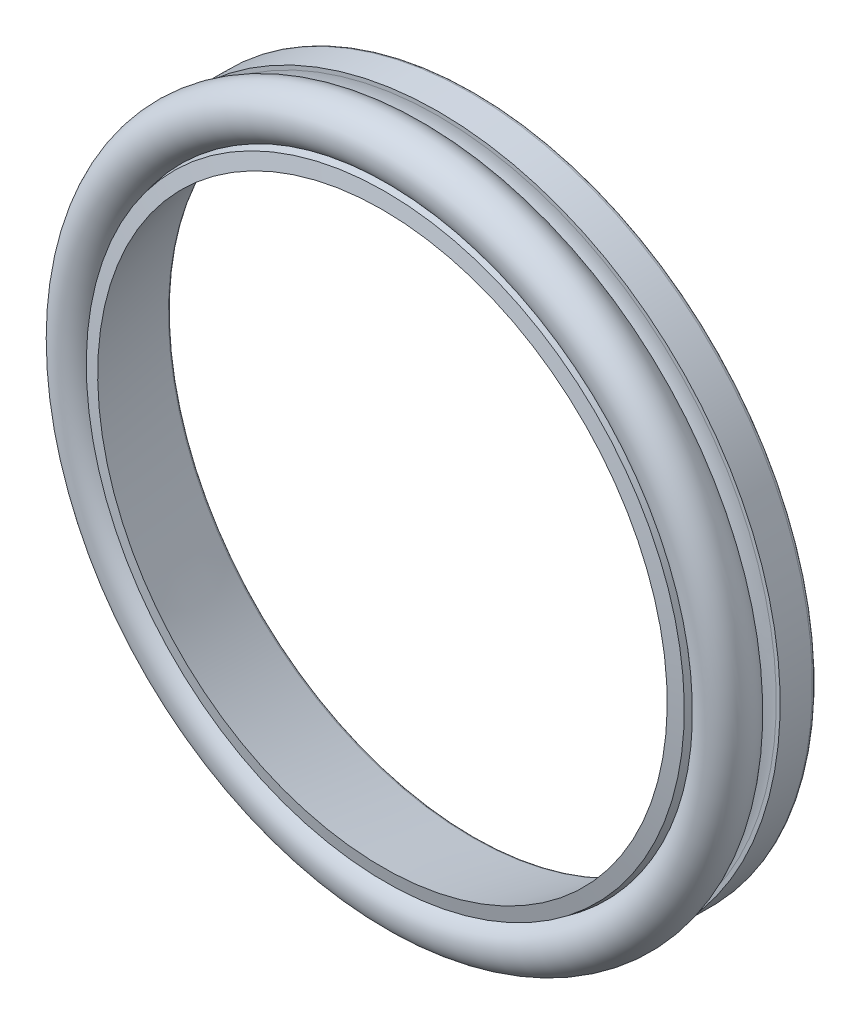
SolidWorks part; units mm, degrees
ref_plane "Front Plane" through (0, 0, 0) normal (0, 0, 1) x (1, 0, 0)
ref_plane "Top Plane" through (0, 0, 0) normal (0, 1, 0) x (1, 0, 0)
ref_plane "Right Plane" through (0, 0, 0) normal (1, 0, 0) x (0, 0, -1)
sketch "Sketch1" plane through (0, 0, 0) normal (1, 0, 0) x (0, 0, -1)
  line L0 (21.2661, 18.606) -> (21.2661, -18.394) construction
  line L1 (-1.9, 18) -> (0, 18)
  line L2 (9.7482, 15.6877) -> (9.7482, -15.5723) construction
  line L3 (0, 18) -> (0, 16)
  line L4 (-4.85, 15) -> (0, 16)
  line L5 (-4.7, 15.75) -> (-4.85, 15)
  line L6 (0, 0) -> (-22.1313, 0) construction
  line L7 (9.7482, 0.0577) -> (29.7477, 0.0577) construction
  line L8 (0, 0) -> (24.9749, 0) construction
  line L9 (-1.9, 18) -> (-1.9, 17.794)
  line L10 (-4.7, 15.75) -> (-3.3365, 16.0311)
  arc A0 (-1.9, 18) -> (-4.7, 15.75) centre (-5.6782, 19.8345) cw construction
  arc A1 (-1.9, 17.794) -> (-3.3365, 16.0311) centre (-3.7, 17.794) cw
  dimension "D2" = 32
  dimension "D9" = 4.2
  dimension "D10" = 1.8
  dimension "D1" = 37
  dimension "D3" = 30
  dimension "D4" = 31.5
  dimension "D5" = 4.85
  dimension "D6" = 4.7
  dimension "D7" = 36
  dimension "D8" = 1.9
revolve "Revolve1" add sketch "Sketch1" angle 360 about L6
fillet "Fillet1" radius 0.2 2 edges at (0, 18, 0) (0, 16, 0)
sketch "Sketch2" plane through (0, 0, 0) normal (1, 0, 0) x (0, 0, -1)
  line L0 (0, 0) -> (-13.3756, 0) construction
  line L1 (0, -18) -> (0, 18) construction
  circle A0 centre (-3.69, 17.02) radius 1.31
  dimension "D1" = 31.42
  dimension "D2" = 2.62
  dimension "D3" = 5
revolve "Revolve2" add sketch "Sketch2" angle 360 about L0
